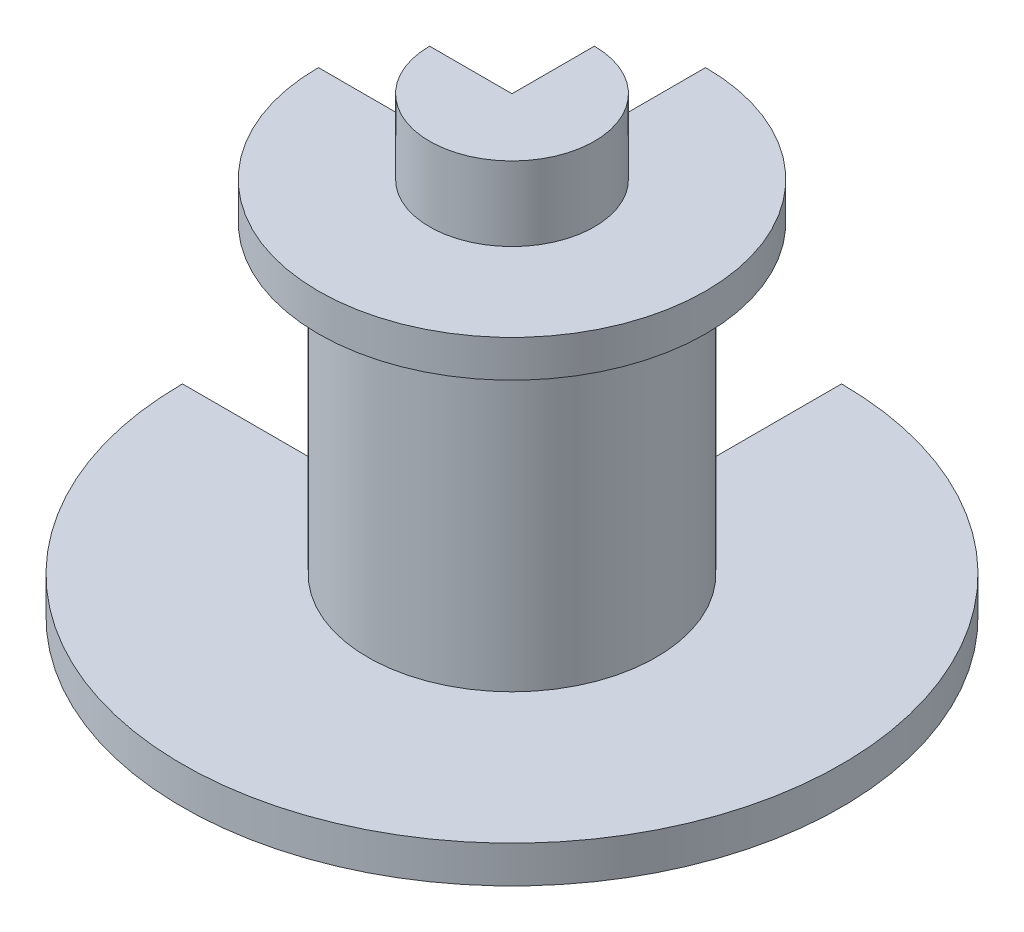
SolidWorks part; units mm, degrees
ref_plane "Front Plane" through (0, 0, 0) normal (0, 0, 1) x (1, 0, 0)
ref_plane "Top Plane" through (0, 0, 0) normal (0, 1, 0) x (1, 0, 0)
ref_plane "Right Plane" through (0, 0, 0) normal (1, 0, 0) x (0, 0, -1)
sketch "Sketch1" plane through (0, 0, 0) normal (0, 0, 1) x (1, 0, 0)
  line L0 (0, 0) -> (-109931.6728, 0) construction
  line L1 (0, 0) -> (0, 109931.6728) construction
  line L2 (0, 0) -> (-80, 0)
  line L3 (-80, 0) -> (-80, 9)
  line L4 (-80, 9) -> (-35, 9)
  line L5 (-35, 9) -> (-35, 83)
  line L6 (-35, 83) -> (-47, 83)
  line L7 (-47, 83) -> (-47, 92)
  line L8 (-47, 92) -> (-20, 92)
  line L9 (-20, 92) -> (-20, 110)
  line L10 (-20, 110) -> (0, 110)
  line L11 (0, 110) -> (0, 0)
  dimension "D1" = 160
  dimension "D2" = 70
  dimension "D3" = 9
  dimension "D4" = 74
  dimension "D5" = 9
  dimension "D6" = 40
  dimension "D7" = 94
  dimension "D8" = 110
revolve "Revolve1" add sketch "Sketch1" angle 270 about L1
